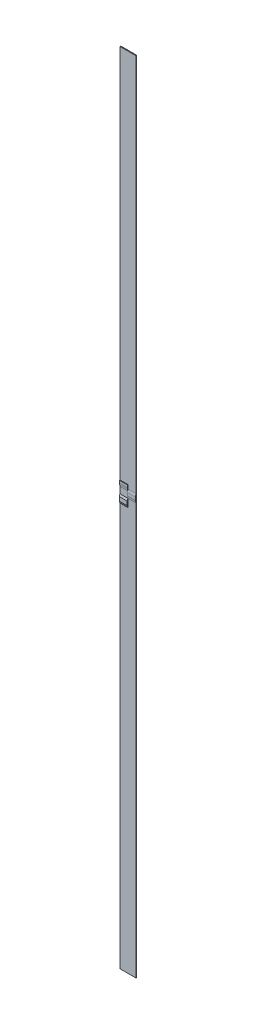
SolidWorks part; units mm, degrees
ref_plane "Front Plane" through (0, 0, 0) normal (0, 0, 1) x (1, 0, 0)
ref_plane "Top Plane" through (0, 0, 0) normal (0, 1, 0) x (1, 0, 0)
ref_plane "Right Plane" through (0, 0, 0) normal (1, 0, 0) x (0, 0, -1)
sketch "Sketch1" plane through (0, 0, 0) normal (0, 0, 1) x (1, 0, 0)
  line L0 (0, 50000) -> (0, 0)
  line L1 (0, 50000) -> (1000, 50000)
  line L3 (0, -50000) -> (1000, -50000)
  line L4 (1000, 50000) -> (1000, -50000)
  line L5 (0, 0) -> (0, -50000)
  dimension "D1" = 1000
  dimension "D2" = 100000
extrude "Boss-Extrude1" add sketch "Sketch1" along normal blind 100
sketch "Sketch2" plane through (0, 0, 0) normal (-1, 0, 0) x (0, 0, 1)
  line L0 (100, 500) -> (190, 750)
  line L1 (0, 50000) -> (100, 50000)
  line L2 (0, 50000) -> (0, -50000)
  line L3 (0, -50000) -> (100, -50000)
  line L4 (100, 50000) -> (100, 1500)
  line L5 (190, 750) -> (190, 1250)
  line L6 (190, 1250) -> (100, 1500)
  line L7 (100, 50000) -> (100, -50000) construction
  line L8 (100, 500) -> (100, -50000)
  line L9 (100, 2300) -> (180, 2700)
  line L10 (180, 2700) -> (180, 3000)
  line L11 (180, 3000) -> (100, 3000)
  line M3 (100, -50000) -> (100, 50000)
  dimension "D1" = 90
  dimension "D2" = 250
  dimension "D3" = 500
  dimension "D4" = 500
  dimension "D5" = 80
  dimension "D6" = 400
  dimension "D7" = 800
  dimension "D8" = 300
extrude "Boss-Extrude2" add sketch "Sketch2" along normal blind 1000 contours L5 L6 L0 M3 | L10 L11 L4 L9
sketch "Sketch3" plane through (1000, 0, 0) normal (1, 0, 0) x (0, 0, -1)
  line L0 (-100, 1500) -> (-160, 1800)
  line L1 (-100, -50000) -> (-100, 50000) construction
  line L2 (-100, 1500) -> (-100, 500) construction
  line L3 (-160, 1800) -> (-160, 2200)
  line L4 (-160, 2200) -> (-100, 2500)
  line L5 (-100, 1500) -> (-100, 2500)
  dimension "D1" = 300
  dimension "D2" = 300
  dimension "D3" = 400
  dimension "D4" = 60
extrude "Boss-Extrude3" add sketch "Sketch3" against normal blind 1000
